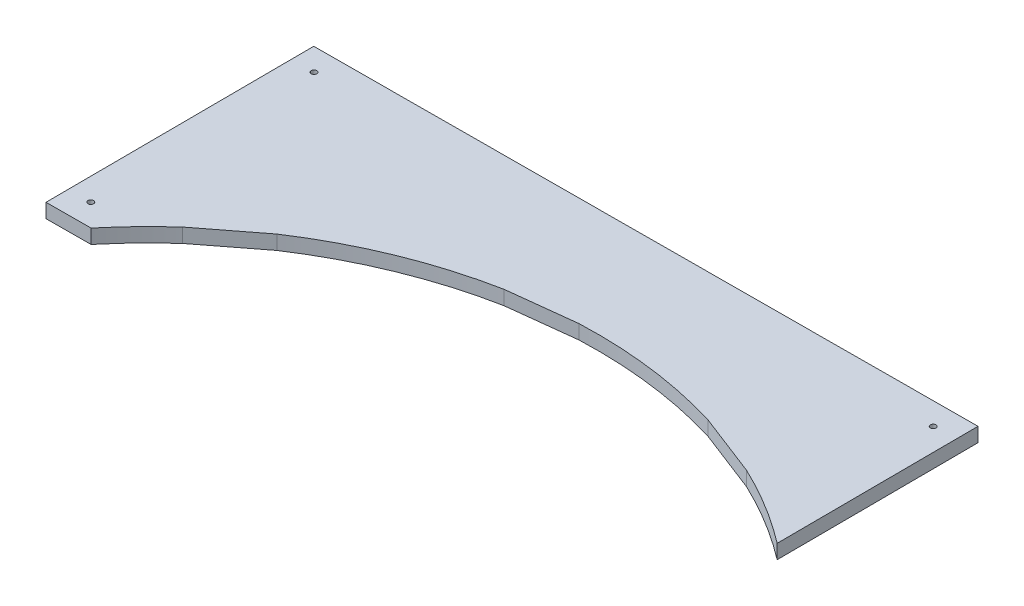
SolidWorks part; units mm, degrees
material "Balsa"
ref_plane "Front Plane" through (0, 0, 0) normal (0, 0, 1) x (1, 0, 0)
ref_plane "Top Plane" through (0, 0, 0) normal (0, 1, 0) x (1, 0, 0)
ref_plane "Right Plane" through (0, 0, 0) normal (1, 0, 0) x (0, 0, -1)
sketch "Sketch1" plane through (0, 0, 0) normal (0, 1, 0) x (1, 0, 0)
  line L0 (19.9998, 0.0912) -> (0, 0)
  line L5 (0, 0) -> (-0.5473, 119.9988)
  line L6 (-0.5473, 119.9988) -> (294.4497, 121.3441)
  line L7 (294.4497, 121.3441) -> (294.8601, 31.3441)
  line L17 (40.0057, 20.8844) -> (63.7564, 39.219)
  line L18 (135.7736, 68.5436) -> (165.7736, 72.0231)
  line L19 (231.7567, 63.5858) -> (259.7794, 52.7343)
  arc A0 (19.9998, 0.0912) -> (40.0057, 20.8844) centre (173.7506, -127.8177) cw
  arc A1 (63.7564, 39.219) -> (135.7736, 68.5436) centre (173.7506, -127.8177) cw
  arc A2 (165.7736, 72.0231) -> (231.7567, 63.5858) centre (173.7506, -127.8177) cw
  arc A3 (259.7794, 52.7343) -> (294.8601, 31.3441) centre (173.7506, -127.8177) cw
  circle A4 centre (9.4982, 110.0445) radius 1.25
  circle A5 centre (9.9543, 10.0455) radius 1.25
  circle A6 centre (284.4954, 111.2986) radius 1.25
  point P17 (0, 0)
  dimension "D5" = 200
  dimension "D8" = 2.5
  dimension "D11" = 2.5
  dimension "D14" = 2.5
  dimension "D1" = 295
  dimension "D2" = 20
  dimension "D3" = 120
  dimension "D4" = 90
  dimension "D6" = 10
  dimension "D7" = 10
  dimension "D9" = 10
  dimension "D10" = 10
  dimension "D12" = 10
  dimension "D13" = 10
extrude "Boss-Extrude1" add sketch "Sketch1" along normal blind 6.35
